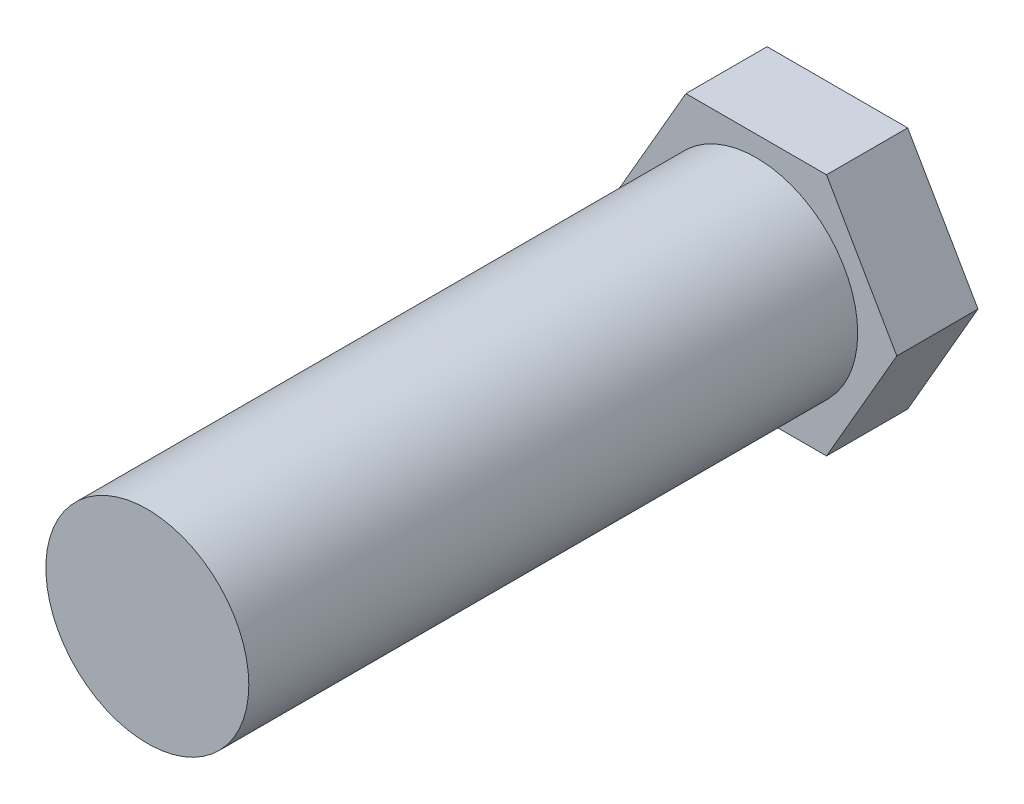
SolidWorks part; units mm, degrees
ref_plane "Front Plane" through (0, 0, 0) normal (0, 0, 1) x (1, 0, 0)
ref_plane "Top Plane" through (0, 0, 0) normal (0, 1, 0) x (1, 0, 0)
ref_plane "Right Plane" through (0, 0, 0) normal (1, 0, 0) x (0, 0, -1)
sketch "Sketch1" plane through (0, 0, 0) normal (0, 0, 1) x (1, 0, 0)
  line L1 (0.1732, 0.3) -> (-0.1732, 0.3)
  line L2 (-0.1732, 0.3) -> (-0.3464, 0)
  line L3 (-0.3464, 0) -> (-0.1732, -0.3)
  line L4 (-0.1732, -0.3) -> (0.1732, -0.3)
  line L5 (0.1732, -0.3) -> (0.3464, 0)
  line L6 (0.3464, 0) -> (0.1732, 0.3)
  circle A0 centre (0, 0) radius 0.3 construction
  dimension "D1" = 0.6
extrude "Boss-Extrude1" add sketch "Sketch1" along normal blind 0.2
sketch "Sketch2" plane through (0, 0, 0.2) normal (0, 0, 1) x (1, 0, 0)
  circle A0 centre (0, 0) radius 0.25
  dimension "D1" = 0.5
extrude "Boss-Extrude2" add sketch "Sketch2" along normal blind 1.5
